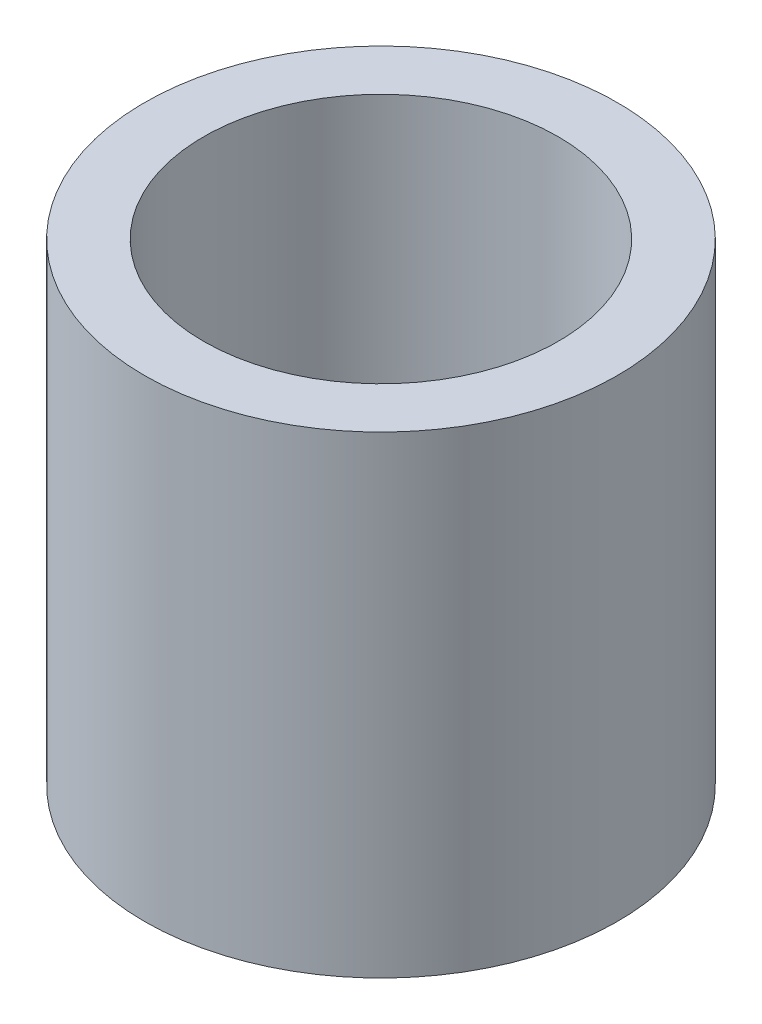
SolidWorks part; units mm, degrees
material "PPE"
ref_plane "Front Plane" through (0, 0, 0) normal (0, 0, 1) x (1, 0, 0)
ref_plane "Top Plane" through (0, 0, 0) normal (0, 1, 0) x (1, 0, 0)
ref_plane "Right Plane" through (0, 0, 0) normal (1, 0, 0) x (0, 0, -1)
sketch "Sketch1" plane through (0, 0, 0) normal (0, 1, 0) x (1, 0, 0)
  circle A0 centre (0, 0) radius 6.35
  dimension "D1" = 12.7
extrude "Boss-Extrude1" add sketch "Sketch1" along normal blind 12.7 contours A0
sketch "Sketch2" plane through (0, 12.7, 0) normal (0, 1, 0) x (1, 0, 0)
  circle A0 centre (0, 0) radius 4.7625
  dimension "D1" = 9.525
extrude "Cut-Extrude1" cut sketch "Sketch2" against normal through all contours A0
